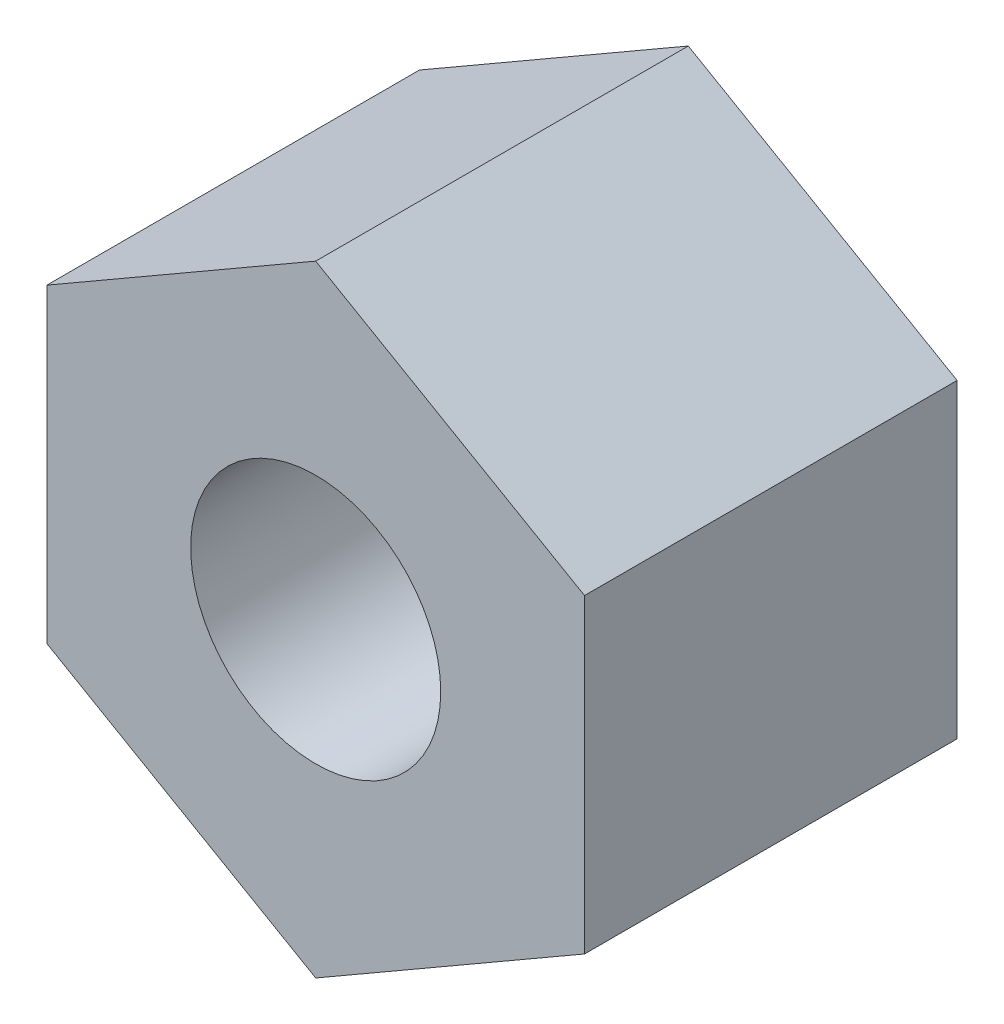
SolidWorks part; units mm, degrees
ref_plane "Front Plane" through (0, 0, 0) normal (1, 0, 0) x (0, 1, 0)
ref_plane "Top Plane" through (0, 0, 0) normal (0, 0, 1) x (0, 1, 0)
ref_plane "Right Plane" through (0, 0, 0) normal (0, 1, 0) x (-1, 0, 0)
sketch "Sketch1" plane through (0, 0, 0) normal (0, 0, 1) x (0, 1, 0)
  line L1 (4.9652, 0) -> (2.4826, 4.3)
  line L2 (2.4826, 4.3) -> (-2.4826, 4.3)
  line L3 (-2.4826, 4.3) -> (-4.9652, 0)
  line L4 (-4.9652, 0) -> (-2.4826, -4.3)
  line L5 (-2.4826, -4.3) -> (2.4826, -4.3)
  line L6 (2.4826, -4.3) -> (4.9652, 0)
  circle A0 centre (0, 0) radius 4.3 construction
  point P1 (4.9652, 0)
  dimension "D1" = 8.6
extrude "Boss-Extrude1" add sketch "Sketch1" along normal blind 5.96
sketch "Sketch2" plane through (0, 0, 0) normal (0, 0, 1) x (0, 1, 0)
  circle A0 centre (0, 0) radius 2
  dimension "D1" = 4
extrude "Cut-Extrude1" cut sketch "Sketch2" along normal up to next
